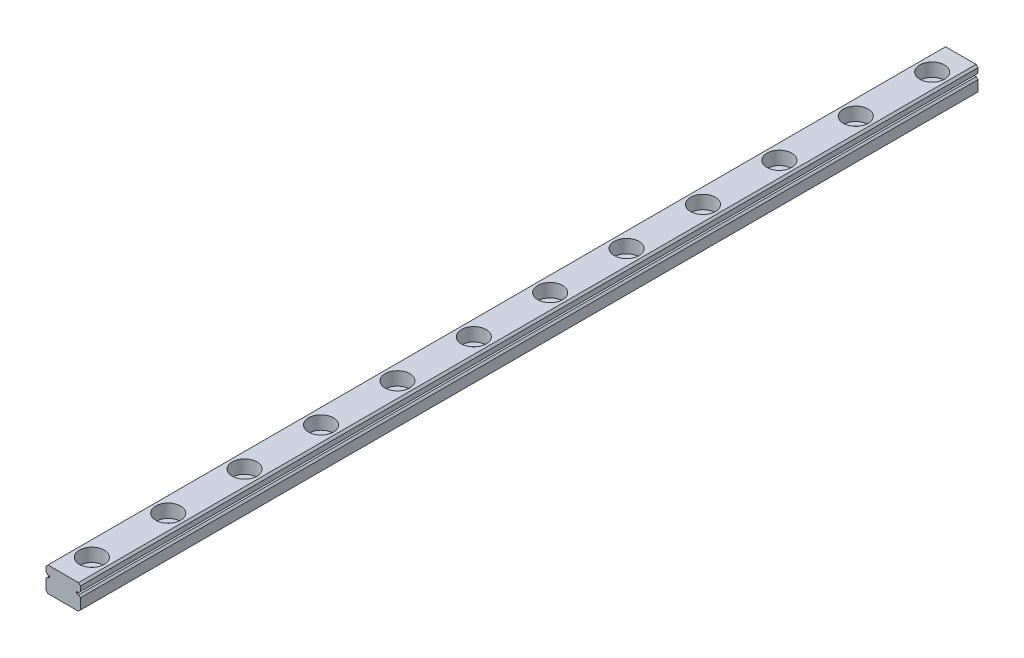
SolidWorks part; units mm, degrees
ref_plane "前视基准面" through (0, 0, 0) normal (0, 0, 1) x (1, 0, 0)
ref_plane "上视基准面" through (0, 0, 0) normal (0, 1, 0) x (1, 0, 0)
ref_plane "右视基准面" through (0, 0, 0) normal (1, 0, 0) x (0, 0, -1)
sketch "草图1" plane through (0, 0, 0) normal (0, 0, 1) x (1, 0, 0)
  line L0 (4.5, 0) -> (-4.5, 0)
  line L1 (-4.5, 0) -> (-4.5, 3.2929)
  line L2 (-4.5, 3.2929) -> (-4.0429, 3.75)
  line L3 (-4.0429, 3.75) -> (-3.5429, 3.75)
  line L4 (-3.5429, 3.75) -> (-3.5429, 4.25)
  line L5 (-3.5429, 4.25) -> (-4.0429, 4.25)
  line L6 (-4.0429, 4.25) -> (-4.5, 4.7071)
  line L7 (-4.5, 4.7071) -> (-4.5, 6.5)
  line L8 (-4.5, 6.5) -> (4.5, 6.5)
  line L9 (0, 6.5) -> (0, 0) construction
  line L10 (4.5, 0) -> (4.5, 3.2929)
  line L11 (4.5, 3.2929) -> (4.0429, 3.75)
  line L12 (4.0429, 3.75) -> (3.5429, 3.75)
  line L13 (3.5429, 3.75) -> (3.5429, 4.25)
  line L14 (3.5429, 4.25) -> (4.0429, 4.25)
  line L15 (4.0429, 4.25) -> (4.5, 4.7071)
  line L16 (4.5, 4.7071) -> (4.5, 6.5)
  circle A0 centre (-4.5, 4) radius 0.5 construction
  point P4 (0, 0)
  point P18 (-3.5429, 4)
  dimension "D4" = 1
  dimension "D1" = 9
  dimension "D2" = 6.5
  dimension "D3" = 0.5
  dimension "D5" = 0.5
  dimension "D6" = 2.5
extrude "凸台-拉伸1" add sketch "草图1" along normal mid plane 235
sketch "草图2" plane through (0, 6.5, 0) normal (0, 1, 0) x (1, 0, 0)
  line L0 (4.5, 117.5) -> (-4.5, 117.5) construction
  circle A0 centre (0, 110) radius 1.75
  circle A1 centre (0, 90) radius 1.75
  circle A2 centre (0, 70) radius 1.75
  circle A3 centre (0, 50) radius 1.75
  circle A4 centre (0, 30) radius 1.75
  circle A5 centre (0, 10) radius 1.75
  circle A6 centre (0, -10) radius 1.75
  circle A7 centre (0, -30) radius 1.75
  circle A8 centre (0, -50) radius 1.75
  circle A9 centre (0, -70) radius 1.75
  circle A10 centre (0, -90) radius 1.75
  circle A11 centre (0, -110) radius 1.75
  dimension "D1" = 7.5
  dimension "D2" = 3.5
  dimension "D4" = 20
  dimension "D3" = 12
extrude "切除-拉伸1" cut sketch "草图2" against normal through all
chamfer "倒角1" distance 0.5 angle 45 4 edges at (-4.5, 6.5, 0) (-4.5, 0, 0) (4.5, 0, 0) (4.5, 6.5, 0)
sketch "草图3" plane through (0, 6.5, 0) normal (0, 1, 0) x (1, 0, 0)
  circle A0 centre (0, 110) radius 3.25
  dimension "D1" = 6.5
extrude "切除-拉伸2" cut sketch "草图3" against normal blind 3.5
pattern_linear "阵列(线性)1" count 12 spacing 20 along (0, 0, 1) of "切除-拉伸2"
